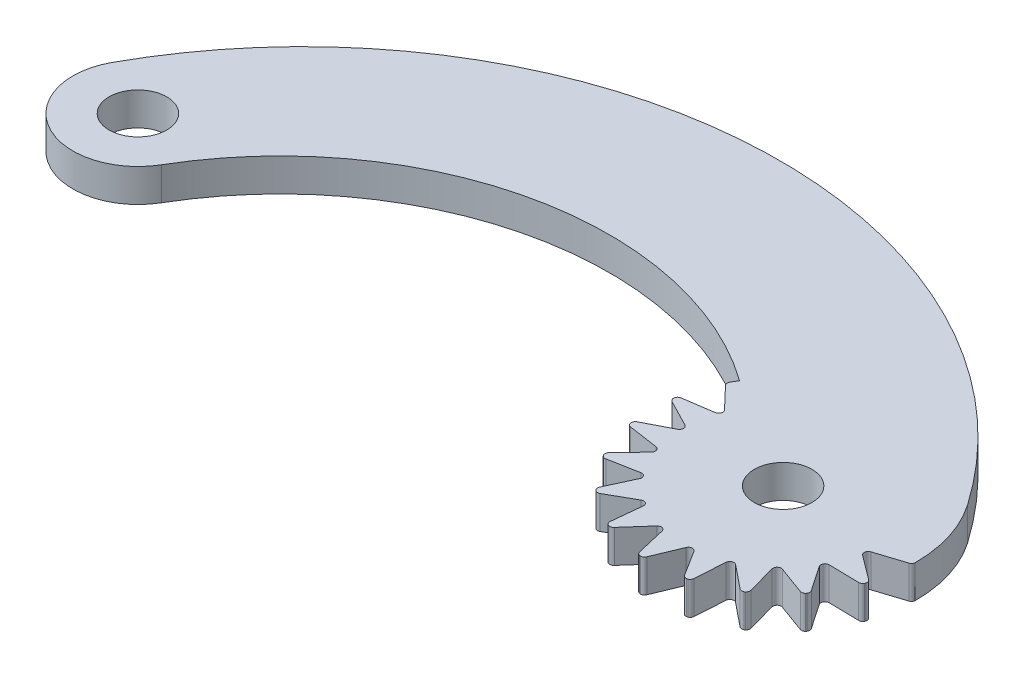
SolidWorks part; units mm, degrees
ref_plane "Front Plane" through (0, 0, 0) normal (0, 0, 1) x (1, 0, 0)
ref_plane "Top Plane" through (0, 0, 0) normal (0, 1, 0) x (1, 0, 0)
ref_plane "Right Plane" through (0, 0, 0) normal (1, 0, 0) x (0, 0, -1)
sketch "Sketch1" plane through (0, 0, 0) normal (0, 1, 0) x (1, 0, 0)
  line L0 (0, 25.5178) -> (0, -32.2544) construction
  line L1 (0, 0) -> (39.1784, 0) construction
  arc A0 (-3.468, 1.8908) -> (3.4127, -1.989) centre (0, 0) ccw
  arc A3 (-3.468, 1.8908) -> (45.776, 4.6037) centre (21.9935, -11.9912) cw
  circle A4 centre (0, 0) radius 1.75
  circle A5 centre (39.1784, 0) radius 1.75
  arc A8 (32.3232, 4.2105) -> (45.776, 4.6037) centre (39.1784, 0) ccw
  arc A9 (3.4127, -1.989) -> (32.3232, 4.2105) centre (20.6922, -12.0597) cw
  dimension "D2" = 7.9
  dimension "D3" = 16.09
  dimension "D4" = 29
  dimension "D5" = 20
  dimension "D6" = 3.5
  dimension "D7" = 3.5
  dimension "D1" = 39.1784
extrude "Boss-Extrude1" add sketch "Sketch1" along normal mid plane 2
sketch "Sketch3" plane through (0, 1, 0) normal (0, 1, 0) x (1, 0, 0)
  line L76 (27.0468, 0) -> (63.8537, 0) construction
  line L77 (39.1784, 0) -> (62.4779, 3.888) construction
  line L155 (45.3137, -0.7987) -> (47.053, -0.2379)
  line L156 (45.2406, -1.2367) -> (46.7036, -2.3318)
  line L157 (44.7219, -2.7475) -> (46.5491, -2.7819)
  line L158 (44.5106, -3.1381) -> (45.5387, -4.6489)
  line L159 (43.5295, -4.3986) -> (45.2464, -5.0244)
  line L160 (43.2027, -4.6994) -> (43.6846, -6.4622)
  line L161 (41.8655, -5.5731) -> (43.2862, -6.7225)
  line L162 (41.4587, -5.7515) -> (41.3422, -7.5752)
  line L163 (39.9103, -6.1436) -> (40.8808, -7.692)
  line L164 (39.4677, -6.1803) -> (38.7653, -7.8673)
  line L165 (37.8758, -6.0484) -> (38.291, -7.828)
  line L166 (37.4453, -5.9393) -> (36.2331, -7.3069)
  line L167 (35.9825, -5.2977) -> (35.7973, -7.1158)
  line L168 (35.6107, -5.0548) -> (34.0201, -5.9547)
  line L169 (34.4355, -3.973) -> (33.67, -5.6324)
  line L170 (34.1627, -3.6225) -> (32.3662, -3.9572)
  line L171 (33.4025, -2.2177) -> (32.1397, -3.5386)
  line L172 (33.2583, -1.7976) -> (31.4504, -1.5308)
  line L173 (32.9953, -0.2221) -> (31.372, -1.0614)
  line L174 (32.9953, 0.2221) -> (31.372, 1.0614)
  line L175 (33.2583, 1.7976) -> (31.4504, 1.5308)
  line L176 (33.4025, 2.2177) -> (32.1397, 3.5386)
  line L193 (34.1627, 3.6225) -> (32.3662, 3.9572) [skipped]
  line L194 (35.6107, 5.0548) -> (34.0201, 5.9547) [skipped]
  line L196 (37.4453, 5.9393) -> (36.2331, 7.3069) [skipped]
  line L197 (43.2027, 4.6994) -> (43.6846, 6.4622) [skipped]
  line L200 (41.4587, 5.7515) -> (41.3422, 7.5752) [skipped]
  line L202 (39.4677, 6.1803) -> (38.7653, 7.8673) [skipped]
  line L204 (44.5106, 3.1381) -> (45.5387, 4.6489) [skipped]
  line L206 (45.2406, 1.2367) -> (46.7036, 2.3318) [skipped]
  arc A139 (46.5491, -2.7819) -> (46.7036, -2.3318) centre (46.5538, -2.532) ccw
  arc A141 (45.1438, -0.9954) -> (45.2263, 0) centre (39.1784, 0) ccw
  circle A199 centre (39.1784, 0) radius 8.0479 construction
  arc A201 (47.053, -0.2379) -> (47.2263, 0) centre (46.9763, 0) ccw
  arc A202 (45.1438, -0.9954) -> (45.3137, -0.7987) centre (45.3904, -1.0366) cw
  arc A203 (45.1438, -0.9954) -> (45.2406, -1.2367) centre (45.3904, -1.0366) ccw
  arc A204 (44.4974, -2.8785) -> (44.7219, -2.7475) centre (44.7172, -2.9975) cw
  arc A205 (45.2464, -5.0244) -> (45.5387, -4.6489) centre (45.332, -4.7896) ccw
  arc A206 (44.4974, -2.8785) -> (44.5106, -3.1381) centre (44.7172, -2.9975) ccw
  arc A207 (43.2745, -4.4496) -> (43.5295, -4.3986) centre (43.4438, -4.6335) cw
  arc A208 (43.2862, -6.7225) -> (43.6846, -6.4622) centre (43.4434, -6.5281) ccw
  arc A209 (43.2745, -4.4496) -> (43.2027, -4.6994) centre (43.4438, -4.6335) ccw
  arc A210 (41.6078, -5.5385) -> (41.8655, -5.5731) centre (41.7082, -5.7674) cw
  arc A211 (40.8808, -7.692) -> (41.3422, -7.5752) centre (41.0927, -7.5593) ccw
  arc A212 (41.6078, -5.5385) -> (41.4587, -5.7515) centre (41.7082, -5.7674) ccw
  arc A213 (39.6778, -6.0272) -> (39.9103, -6.1436) centre (39.6985, -6.2764) cw
  arc A214 (38.291, -7.828) -> (38.7653, -7.8673) centre (38.5345, -7.7713) ccw
  arc A215 (39.6778, -6.0272) -> (39.4677, -6.1803) centre (39.6985, -6.2764) ccw
  arc A216 (37.6937, -5.8628) -> (37.8758, -6.0484) centre (37.6324, -6.1052) cw
  arc A217 (35.7973, -7.1158) -> (36.2331, -7.3069) centre (36.046, -7.1411) ccw
  arc A218 (37.6937, -5.8628) -> (37.4453, -5.9393) centre (37.6324, -6.1052) ccw
  arc A219 (35.8705, -5.0631) -> (35.9825, -5.2977) centre (35.7338, -5.2724) cw
  arc A220 (33.67, -5.6324) -> (34.0201, -5.9547) centre (33.897, -5.7371) ccw
  arc A221 (35.8705, -5.0631) -> (35.6107, -5.0548) centre (35.7338, -5.2724) ccw
  arc A222 (34.4058, -3.7147) -> (34.4355, -3.973) centre (34.2085, -3.8682) cw
  arc A223 (32.1397, -3.5386) -> (32.3662, -3.9572) centre (32.3204, -3.7114) ccw
  arc A224 (34.4058, -3.7147) -> (34.1627, -3.6225) centre (34.2085, -3.8682) ccw
  arc A225 (33.4582, -1.9637) -> (33.4025, -2.2177) centre (33.2218, -2.0449) cw
  arc A226 (31.372, -1.0614) -> (31.4504, -1.5308) centre (31.4869, -1.2835) ccw
  arc A227 (33.4582, -1.9637) -> (33.2583, -1.7976) centre (33.2218, -2.0449) ccw
  arc A228 (33.1305, 0) -> (32.9953, -0.2221) centre (32.8805, 0) cw
  arc A229 (31.4504, 1.5308) -> (31.372, 1.0614) centre (31.4869, 1.2835) ccw
  arc A230 (33.1305, 0) -> (32.9953, 0.2221) centre (32.8805, 0) ccw
  arc A231 (33.4582, 1.9637) -> (33.2583, 1.7976) centre (33.2218, 2.0449) cw
  arc A232 (32.1005, 3.8304) -> (32.1397, 3.5386) centre (32.3204, 3.7114) ccw
  arc A233 (33.4582, 1.9637) -> (33.4025, 2.2177) centre (33.2218, 2.0449) ccw
  arc A256 (32.1005, 3.8304) -> (47.2263, 0) centre (39.1784, 0) ccw
  arc A258 (34.4058, 3.7147) -> (34.1627, 3.6225) centre (34.2085, 3.8682) cw [skipped]
  arc A260 (33.7277, 5.921) -> (33.67, 5.6324) centre (33.897, 5.7371) ccw [skipped]
  arc A261 (35.8705, 5.0631) -> (35.6107, 5.0548) centre (35.7338, 5.2724) cw [skipped]
  arc A263 (36.2331, 7.3069) -> (35.9456, 7.37) centre (36.046, 7.1411) ccw [skipped]
  arc A265 (43.2745, 4.4496) -> (43.2027, 4.6994) centre (43.4438, 4.6335) cw [skipped]
  arc A266 (43.5802, 6.7374) -> (43.2862, 6.7225) centre (43.4434, 6.5281) ccw [skipped]
  arc A268 (41.6078, 5.5385) -> (41.4587, 5.7515) centre (41.7082, 5.7674) cw [skipped]
  arc A269 (41.154, 7.8016) -> (40.8808, 7.692) centre (41.0927, 7.5593) ccw [skipped]
  arc A271 (39.6778, 6.0272) -> (39.4677, 6.1803) centre (39.6985, 6.2764) cw [skipped]
  arc A272 (38.5138, 8.0204) -> (38.291, 7.828) centre (38.5345, 7.7713) ccw [skipped]
  arc A274 (37.6937, 5.8628) -> (37.4453, 5.9393) centre (37.6324, 6.1052) cw [skipped]
  arc A275 (45.5387, 4.6489) -> (45.5293, 4.9431) centre (45.332, 4.7896) ccw [skipped]
  arc A276 (44.4974, 2.8785) -> (44.5106, 3.1381) centre (44.7172, 2.9975) cw [skipped]
  arc A278 (46.7902, 2.6131) -> (46.5491, 2.7819) centre (46.5538, 2.532) ccw [skipped]
  arc A279 (45.1438, 0.9954) -> (45.2406, 1.2367) centre (45.3904, 1.0366) cw [skipped]
  point P182 (39.1784, 0)
  arc M78 (32.3232, 4.2105) -> (45.776, 4.6037) centre (39.1784, 0) ccw
  dimension "D1" = 12.0958
  dimension "D2" = 2
  dimension "D5" = 0.5
  dimension "D6" = 19
  dimension "D3" = 9.474
extrude "Cut-Extrude1" cut sketch "Sketch3" against normal blind 10 contours A231 A233 L176 A232 A229 L175 M78 | A228 A230 L174 A229 A226 L173 M78 | A225 A227 L172 A226 A223 L171 M78 | A222 A224 L170 A223 A220 L169 M78 | A219 A221 L168 A220 A217 L167 M78 | A216 A218 L166 A217 A214 L165 M78 | A213 A215 L164 A214 A211 L163 M78 | A210 A212 L162 A211 A208 L161 M78 | A207 A209 L160 A208 A205 L159 M78 | A204 A206 L158 A205 A139 L157 M78 | A202 A203 L156 A139 A201 L155 M78
